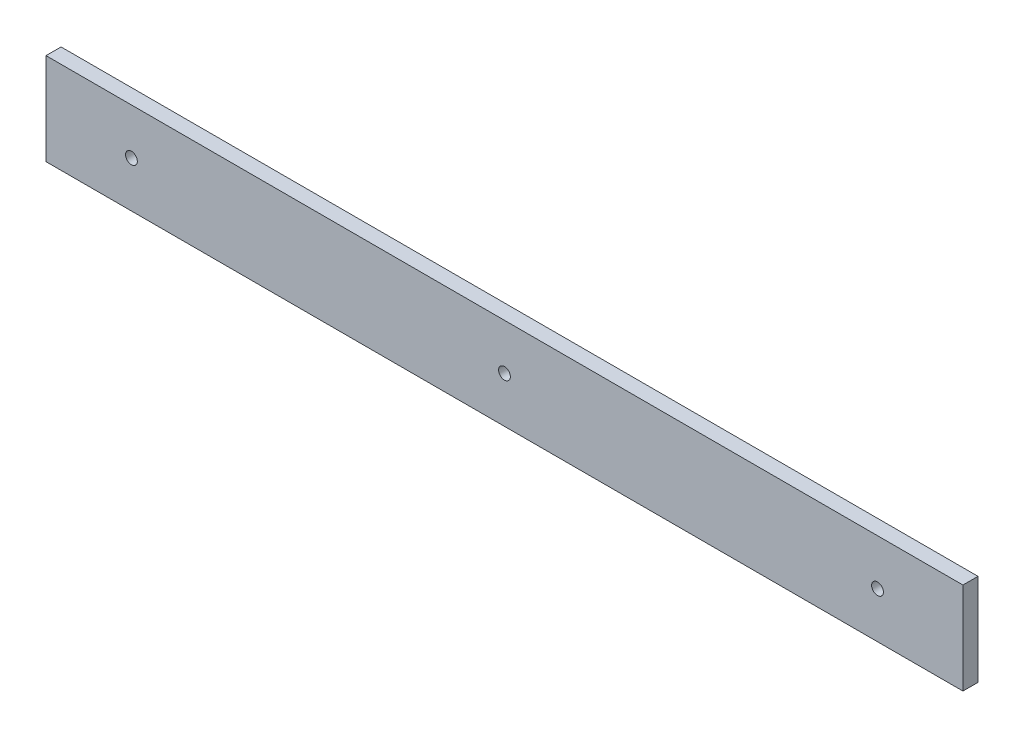
SolidWorks part; units mm, degrees
material "1100-H12 Rod (SS)"
ref_plane "X-Y Datum" through (0, 0, 0) normal (0, 0, 1) x (1, 0, 0)
ref_plane "X-Z Datum" through (0, 0, 0) normal (0, 1, 0) x (1, 0, 0)
ref_plane "Y-Z Datum" through (0, 0, 0) normal (1, 0, 0) x (0, 0, -1)
sketch "Sketch1" plane through (0, 0, 0) normal (0, 0, 1) x (1, 0, 0)
  line L1 (0, 0) -> (97.398, 0)
  line L2 (0, 0) -> (0, 9.7577)
  line L3 (0, 9.7577) -> (97.398, 9.7577)
  line L4 (97.398, 0) -> (97.398, 9.7577)
extrude "Boss-Extrude1" add sketch "Sketch1" along normal blind 1.6002 contours L3 L4 L1 L2
sketch "Sketch2" plane through (0, 0, 1.6002) normal (0, 0, 1) x (1, 0, 0)
  line L0 (0, 4.8788) -> (9.075, 4.8788) construction
  line L1 (0, 0) -> (0, 9.7577) construction
  line L2 (9.075, 4.8788) -> (48.699, 4.8788) construction
  line L3 (97.398, 4.8788) -> (88.323, 4.8788) construction
  line L4 (97.398, 0) -> (97.398, 9.7577) construction
  circle A0 centre (9.075, 4.8788) radius 0.625
  circle A1 centre (48.699, 4.8788) radius 0.625
  circle A2 centre (88.323, 4.8788) radius 0.625
extrude "Cut-Extrude1" cut sketch "Sketch2" against normal through all
